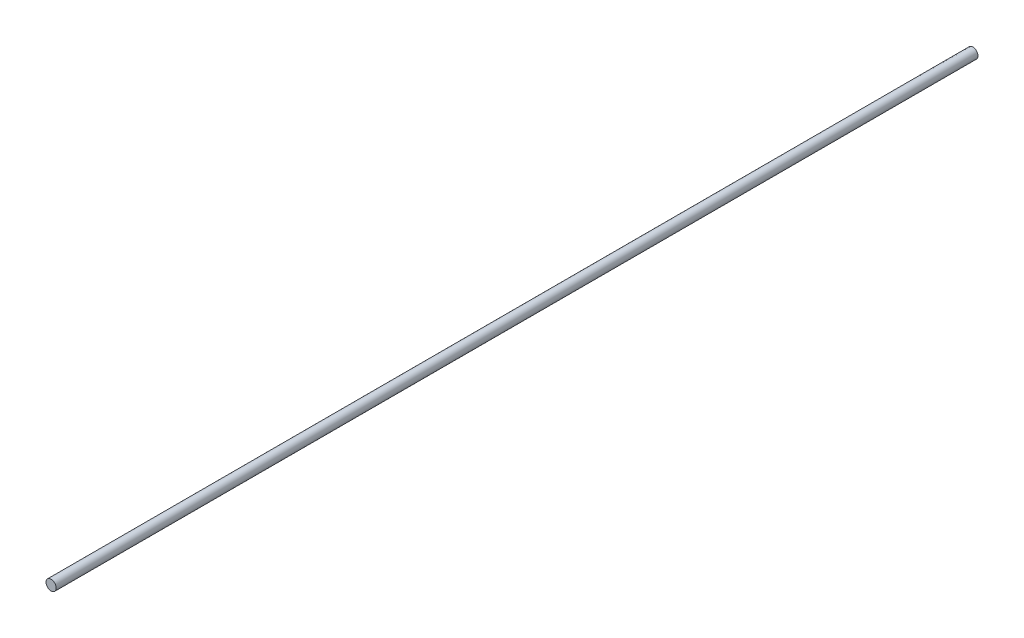
SolidWorks part; units mm, degrees
ref_plane "Plan de face" through (0, 0, 0) normal (0, 0, 1) x (1, 0, 0)
ref_plane "Plan de dessus" through (0, 0, 0) normal (0, 1, 0) x (1, 0, 0)
ref_plane "Plan de droite" through (0, 0, 0) normal (1, 0, 0) x (0, 0, -1)
sketch "Esquisse1" plane through (0, 0, 0) normal (0, 0, 1) x (1, 0, 0)
  circle A0 centre (0, 0) radius 4
  dimension "D1" = 8
extrude "Boss.-Extru.1" add sketch "Esquisse1" along normal blind 722
